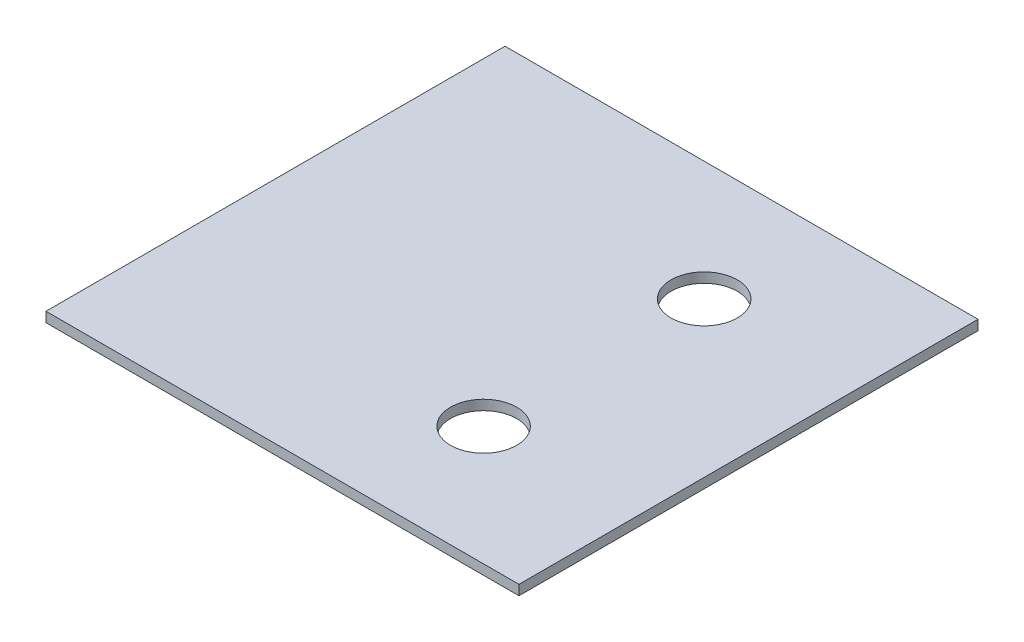
SolidWorks part; units mm, degrees
ref_plane "Front" through (0, 0, 0) normal (0, 0, 1) x (1, 0, 0)
ref_plane "Top" through (0, 0, 0) normal (0, 1, 0) x (1, 0, 0)
ref_plane "Right" through (0, 0, 0) normal (1, 0, 0) x (0, 0, -1)
sketch "Sketch1" plane through (0, 0, 0) normal (0, 1, 0) x (1, 0, 0)
  line L1 (-11.9, 11.55) -> (11.9, 11.55)
  line L2 (-11.9, 11.55) -> (-11.9, -11.55)
  line L3 (-11.9, -11.55) -> (11.9, -11.55)
  line L4 (11.9, 11.55) -> (11.9, -11.55)
  line L5 (-11.9, 11.55) -> (11.9, -11.55) construction
  line L6 (-11.9, -11.55) -> (11.9, 11.55) construction
  point P0 (0, 0)
  dimension "D1" = 23.8
  dimension "D2" = 23.1
extrude "Boss-Extrude1" add sketch "Sketch1" along normal blind 0.5
sketch "Sketch2" plane through (0, 0.5, 0) normal (0, 1, 0) x (1, 0, 0)
  circle A0 centre (4.1214, 5.5494) radius 1.665
  circle A1 centre (4.1214, -5.55) radius 1.665
  dimension "D1" = 3.33
extrude "Cut-Extrude1" cut sketch "Sketch2" against normal up to next
